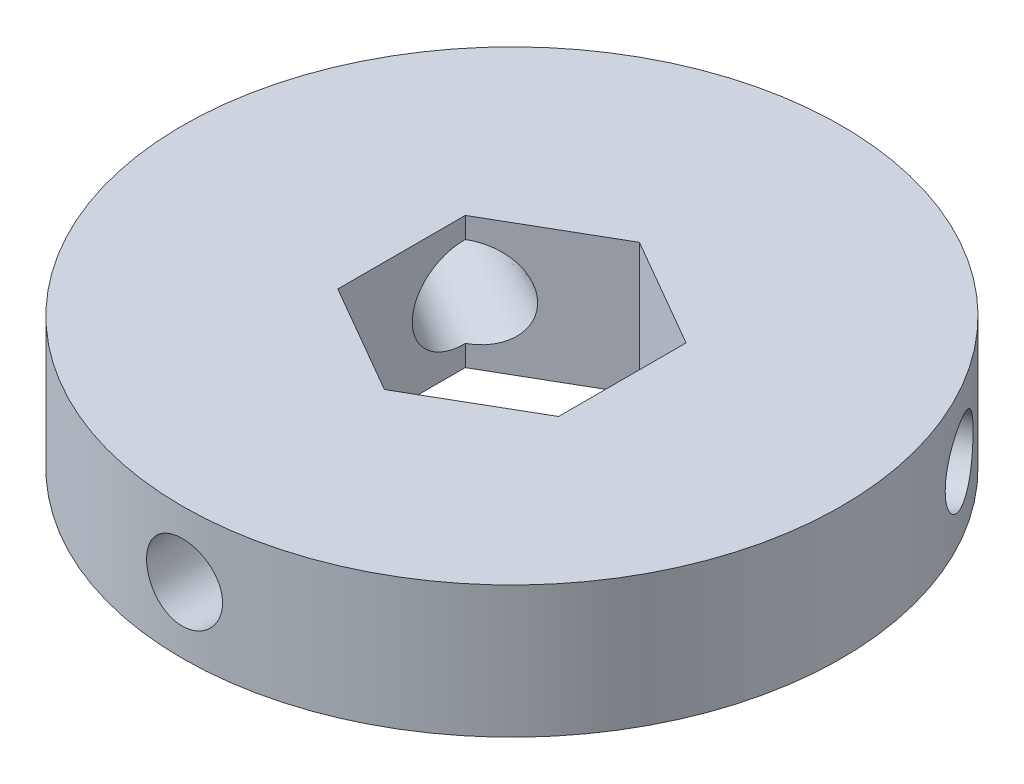
SolidWorks part; units mm, degrees
ref_plane "Front Plane" through (0, 0, 0) normal (0, 0, 1) x (1, 0, 0)
ref_plane "Top Plane" through (0, 0, 0) normal (0, 1, 0) x (1, 0, 0)
ref_plane "Right Plane" through (0, 0, 0) normal (1, 0, 0) x (0, 0, -1)
sketch "Sketch1" plane through (0, 0, 0) normal (0, 1, 0) x (1, 0, 0)
  line L7 (0, 5.25) -> (-4.5466, 2.625) construction
  line L8 (-4.5466, 2.625) -> (-4.5466, -2.625) construction
  line L9 (-4.5466, -2.625) -> (0, -5.25) construction
  line L10 (0, -5.25) -> (4.5466, -2.625) construction
  line L11 (4.5466, -2.625) -> (4.5466, 2.625) construction
  line L12 (4.5466, 2.625) -> (0, 5.25) construction
  line L13 (0, 3.8682) -> (-3.35, 1.9341)
  line L14 (-3.35, 1.9341) -> (-3.35, -1.9341)
  line L15 (-3.35, -1.9341) -> (0, -3.8682)
  line L16 (0, -3.8682) -> (3.35, -1.9341)
  line L17 (3.35, -1.9341) -> (3.35, 1.9341)
  line L18 (3.35, 1.9341) -> (0, 3.8682)
  circle A0 centre (0, 0) radius 10
  circle A1 centre (0, 0) radius 3.8682 construction
  circle A2 centre (0, 0) radius 5.25 construction
  circle A7 centre (0, 0) radius 3.35 construction
  dimension "D1" = 20
  dimension "D2" = 6.7
  dimension "D3" = 10.5
extrude "Boss-Extrude1" add sketch "Sketch1" along normal mid plane 4
sketch "Sketch2" plane through (0, 0, 0) normal (0, 0, 1) x (1, 0, 0)
  line L0 (10, 0) -> (-10, 0) construction
  circle A0 centre (0, 0) radius 1.5
  dimension "D1" = 1.5
extrude "Cut-Extrude1" cut sketch "Sketch2" along normal up to surface draft 2 up to face at (0, 2, 10)
pattern_circular "CirPattern1" count 3 over 360 about axis through (0, 2, 0) along (0, -1, 0) of "Cut-Extrude1"
